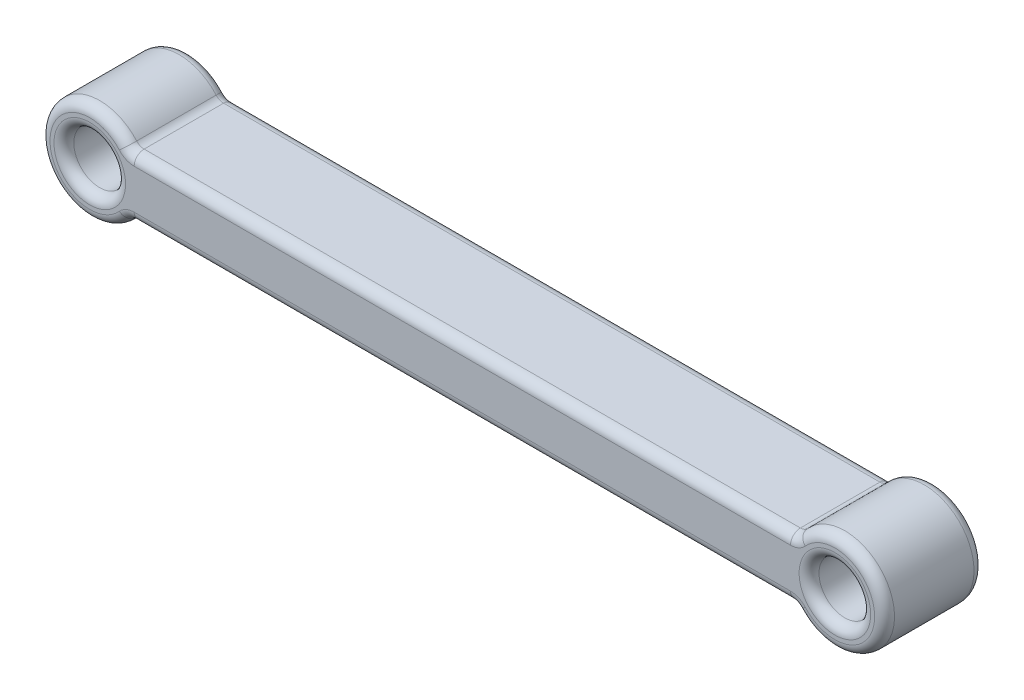
SolidWorks part; units mm, degrees
ref_plane "Front Plane" through (0, 0, 0) normal (0, 0, 1) x (1, 0, 0)
ref_plane "Top Plane" through (0, 0, 0) normal (0, 1, 0) x (1, 0, 0)
ref_plane "Right Plane" through (0, 0, 0) normal (1, 0, 0) x (0, 0, -1)
sketch "Sketch1" plane through (0, 0, 0) normal (0, 0, 1) x (1, 0, 0)
  line L0 (0, 0) -> (-75, 0) construction
  line L1 (-71, 3) -> (-4, 3)
  line L2 (-71, -3) -> (-4, -3)
  arc A0 (-71, 3) -> (-71, -3) centre (-75, 0) ccw
  arc A1 (-4, -3) -> (-4, 3) centre (0, 0) ccw
  circle A2 centre (-75, 0) radius 2.6
  circle A3 centre (0, 0) radius 2.6
  dimension "D4" = 5.2
  dimension "D5" = 5
  dimension "D6" = 5.2
  dimension "D7" = 5
  dimension "D1" = 75
  dimension "D2" = 3
  dimension "D3" = 3
extrude "Boss-Extrude1" add sketch "Sketch1" along normal blind 10
fillet "Fillet1" radius 1 16 edges at (-4, 3, 5) (-71, 3, 5) (-71, -3, 5) (-4, -3, 5) (2.6, 0, 0) (-72.4, 0, 0) (-37.5, -3, 0) (5, 0, 0) (-37.5, 3, 0) (-80, 0, 0) (2.6, 0, 10) (-37.5, 3, 10) (5, 0, 10) (-37.5, -3, 10) (-80, 0, 10) (-72.4, 0, 10)
